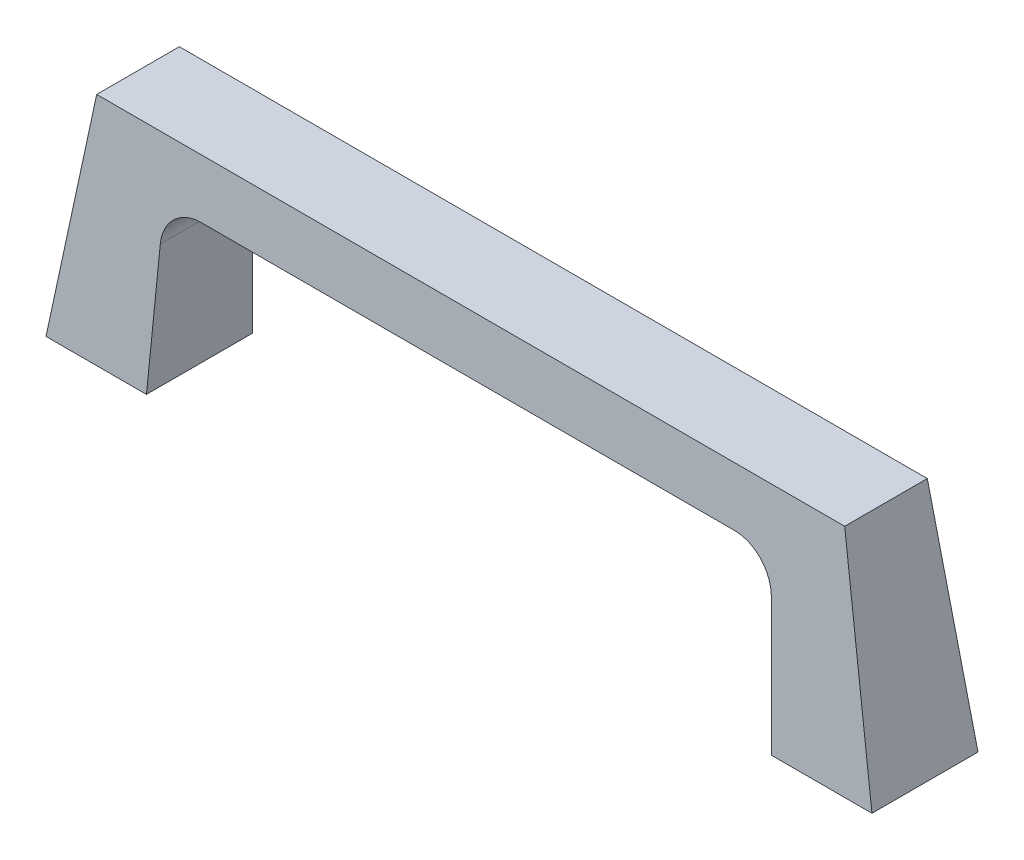
SolidWorks part; units mm, degrees
ref_plane "Front Plane" through (0, 0, 0) normal (0, 0, 1) x (1, 0, 0)
ref_plane "Top Plane" through (0, 0, 0) normal (0, 1, 0) x (1, 0, 0)
ref_plane "Right Plane" through (0, 0, 0) normal (1, 0, 0) x (0, 0, -1)
sketch "Sketch1" plane through (0, 0, 0) normal (0, 0, 1) x (1, 0, 0)
  line L0 (65, 0) -> (-65, 0) construction
  line L1 (0, 0) -> (0, 30) construction
  line L2 (-74, 0) -> (-67.0136, 40)
  line L3 (-74, 0) -> (-56, 0)
  line L7 (-67.0136, 40) -> (67.0136, 40)
  line L8 (47.7533, 30) -> (-47.7533, 30)
  line L9 (-54.7432, 23.3758) -> (-56, 0)
  line L10 (54.7432, 23.3758) -> (56, 0)
  line L11 (74, 0) -> (56, 0)
  line L12 (74, 0) -> (67.0136, 40)
  arc A0 (-47.7533, 30) -> (-54.7432, 23.3758) centre (-47.7533, 23) ccw
  arc A1 (47.7533, 30) -> (54.7432, 23.3758) centre (47.7533, 23) cw
  point P8 (-65, 0)
  point P20 (0, 40)
  dimension "D5" = 7
  dimension "D1" = 130
  dimension "D2" = 148
  dimension "D3" = 40
  dimension "D4" = 30
extrude "Boss-Extrude1" add sketch "Sketch1" along normal blind 19
draft "Draft1" type of draft neutral plane draft angle 3 neutral plane "Top Plane" faces to draft 2 face at (0, 18.9538, 0) face at (0, 18.9538, 19) neutral plane through (0, 0, 0) neutral plane normal (0, 1, 0) parameters "D1"=3
sketch "Sketch2" plane through (0, 0, 0) normal (0, -1, 0) x (1, 0, 0)
  line L0 (-74, 9.5) -> (-56, 9.5) construction
  line L1 (-74, 19) -> (-74, 0) construction
  line L2 (-56, 19) -> (-56, 0) construction
  point P6 (-65, 9.5)
hole_wizard "M6x1.0 Tapped Hole1" positions "3DSketch1" profile "Sketch3" tap size "M6x1.0" standard "BSI"
sketch3d "3DSketch1"
  point P0 (-65, 0, 9.5)
sketch "Sketch3" plane through (-65, 0, 9.5) normal (1, 0, 0) x (0, 0, -1)
  line L0 (0, 0) -> (0, 16.5022)
  line L1 (0, 16.5022) -> (2.5, 15)
  line L2 (2.5, 15) -> (2.5, 0)
  line L5 (2.5, 0) -> (0, 0)
  line L10 (0, 16.5022) -> (-2.5, 15) construction
  line L11 (0, -6.35) -> (0, 107.95) construction
  dimension "Tap Drill Dia." = 5
  dimension "Tap Drill Depth" = 15
  dimension "Drill Angle" = 118
cosmetic thread "Hole Thread1" parameters "D1"=12, "D2"=6
mirror "Mirror1" about plane through (0, 0, 0) normal (1, 0, 0) of "M6x1.0 Tapped Hole1"
